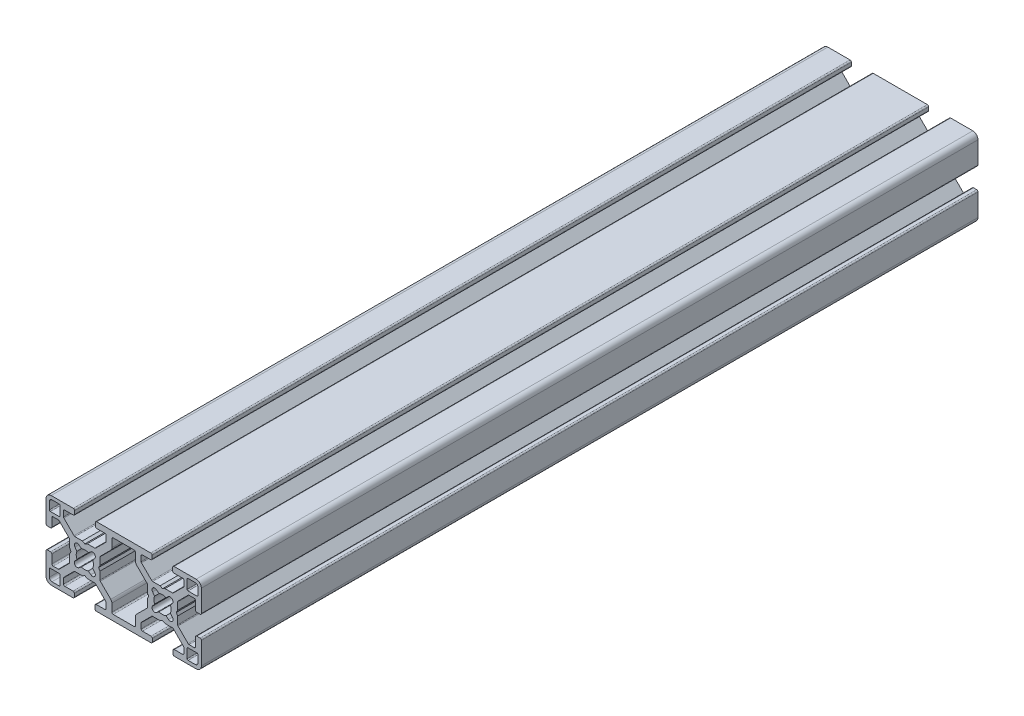
SolidWorks part; units mm, degrees
material "6105-T5 Aluminum"
ref_plane "Front Plane" through (0, 0, 0) normal (0, 0, 1) x (1, 0, 0)
ref_plane "Top Plane" through (0, 0, 0) normal (0, 1, 0) x (1, 0, 0)
ref_plane "Right Plane" through (0, 0, 0) normal (1, 0, 0) x (0, 0, -1)
sketch "Sketch1" plane through (0, 0, 0) normal (0, 0, -1) x (1, 0, 0)
  line L0 (13.319, 9.5) -> (9.88, 9.5)
  line L1 (9.5, 9.88) -> (9.5, 13.319)
  line L2 (9.881, 13.7) -> (12.7, 13.7)
  line L3 (13.7, 12.7) -> (13.7, 9.881)
  line L4 (13.7, -9.881) -> (13.7, -12.7)
  line L5 (12.7, -13.7) -> (9.881, -13.7)
  line L6 (9.5, -13.319) -> (9.5, -9.88)
  line L7 (9.88, -9.5) -> (13.319, -9.5)
  line L8 (1.3394, 3.0433) -> (2.3185, 3.8251)
  line L9 (3.8251, 2.3185) -> (3.0433, 1.3394)
  line L10 (3.0433, -1.3394) -> (3.8251, -2.3185)
  line L11 (2.3185, -3.8251) -> (1.3394, -3.0433)
  line L12 (-1.3292, -3.0477) -> (-2.3144, -3.8343)
  line L13 (-3.821, -2.3278) -> (-3.0392, -1.3486)
  line L14 (-3.0433, 1.3394) -> (-3.8251, 2.3185)
  line L15 (-2.3185, 3.8251) -> (-1.3394, 3.0433)
  line L16 (-10.45, 12.3) -> (-10.45, 9.2682)
  line L17 (-10.0106, 8.2075) -> (-5.9811, 4.178)
  line L18 (-5.8347, 3.8245) -> (-5.8347, 0.8875)
  line L19 (-5.8347, 0.8875) -> (-5.3247, -0.0625)
  line L20 (-5.3247, -0.0625) -> (-5.8347, -1.0125)
  line L21 (-5.8347, -1.0125) -> (-5.8347, -3.8245)
  line L22 (-5.9811, -4.178) -> (-10.0106, -8.2075)
  line L23 (-10.45, -9.2682) -> (-10.45, -12.3)
  line L24 (-10.95, -12.8) -> (-19.05, -12.8)
  line L25 (-19.55, -12.3) -> (-19.55, -9.2682)
  line L26 (-19.9893, -8.2075) -> (-24.0188, -4.178)
  line L27 (-24.1653, -3.8245) -> (-24.1653, -1.0125)
  line L28 (-24.1653, -1.0125) -> (-24.6753, -0.0625)
  line L29 (-24.6753, -0.0625) -> (-24.1653, 0.8875)
  line L30 (-24.1653, 0.8875) -> (-24.1653, 3.8245)
  line L31 (-24.0188, 4.178) -> (-19.9893, 8.2075)
  line L32 (-19.55, 9.2682) -> (-19.55, 12.3)
  line L33 (-19.05, 12.8) -> (-10.95, 12.8)
  line L34 (-28.6606, 3.0433) -> (-27.6814, 3.8251)
  line L35 (-26.1749, 2.3185) -> (-26.9566, 1.3394)
  line L36 (-26.9566, -1.3394) -> (-26.1749, -2.3185)
  line L37 (-27.6814, -3.8251) -> (-28.6606, -3.0433)
  line L38 (-31.3292, -3.0477) -> (-32.3143, -3.8343)
  line L39 (-33.8209, -2.3278) -> (-33.0391, -1.3486)
  line L40 (-33.0432, 1.3394) -> (-33.825, 2.3185)
  line L41 (-32.3184, 3.8251) -> (-31.3393, 3.0433)
  line L42 (-39.8809, -13.7) -> (-42.6999, -13.7)
  line L43 (-43.6999, -12.7) -> (-43.6999, -9.881)
  line L44 (-43.3189, -9.5) -> (-39.8799, -9.5)
  line L45 (-39.4999, -9.88) -> (-39.4999, -13.319)
  line L46 (-43.6999, 9.881) -> (-43.6999, 12.7)
  line L47 (-42.6999, 13.7) -> (-39.8809, 13.7)
  line L48 (-39.4999, 13.319) -> (-39.4999, 9.88)
  line L49 (-39.8799, 9.5) -> (-43.3189, 9.5)
  line L50 (-25.9374, -13.2425) -> (-25.9374, -14.5)
  line L51 (-25.4374, -15) -> (-4.5625, -15)
  line L52 (-4.0625, -14.5) -> (-4.0625, -13.2425)
  line L53 (-4.5625, -12.7425) -> (-7.7325, -12.7425)
  line L54 (-8.25, -12.2428) -> (-8.25, -10.2602)
  line L55 (-8.1035, -9.9067) -> (-4.178, -5.9811)
  line L56 (-3.8245, -5.8347) -> (-0.95, -5.8347)
  line L57 (-0.95, -5.8347) -> (0, -5.3247)
  line L58 (0, -5.3247) -> (0.95, -5.8347)
  line L59 (0.95, -5.8347) -> (3.8245, -5.8347)
  line L60 (4.178, -5.9811) -> (8.1035, -9.9067)
  line L61 (8.25, -10.2602) -> (8.25, -12.2428)
  line L62 (7.7325, -12.7425) -> (4.4375, -12.7425)
  line L63 (3.9375, -13.2425) -> (3.9375, -14.5)
  line L64 (4.4375, -15) -> (13, -15)
  line L65 (15, -13) -> (15, -4.5625)
  line L66 (14.5, -4.0625) -> (13.2425, -4.0625)
  line L67 (12.7425, -4.5625) -> (12.7425, -7.7325)
  line L68 (12.2428, -8.25) -> (10.2602, -8.25)
  line L69 (9.9067, -8.1035) -> (5.9811, -4.178)
  line L70 (5.8347, -3.8245) -> (5.8347, -1.0125)
  line L71 (5.8347, -1.0125) -> (5.3247, -0.0625)
  line L72 (5.3247, -0.0625) -> (5.8347, 0.8875)
  line L73 (5.8347, 0.8875) -> (5.8347, 3.8245)
  line L74 (5.9811, 4.178) -> (9.9067, 8.1035)
  line L75 (10.2602, 8.25) -> (12.2428, 8.25)
  line L76 (12.7425, 7.7325) -> (12.7425, 4.4375)
  line L77 (13.2425, 3.9375) -> (14.5, 3.9375)
  line L78 (15, 4.4375) -> (15, 13)
  line L79 (13, 15) -> (4.5625, 15)
  line L80 (4.0625, 14.5) -> (4.0625, 13.2425)
  line L81 (4.5625, 12.7425) -> (7.7325, 12.7425)
  line L82 (8.25, 12.2428) -> (8.25, 10.2602)
  line L83 (8.1035, 9.9067) -> (4.178, 5.9811)
  line L84 (3.8245, 5.8347) -> (0.95, 5.8347)
  line L85 (0.95, 5.8347) -> (0, 5.3247)
  line L86 (0, 5.3247) -> (-0.95, 5.8347)
  line L87 (-0.95, 5.8347) -> (-3.8245, 5.8347)
  line L88 (-4.178, 5.9811) -> (-8.1035, 9.9067)
  line L89 (-8.25, 10.2602) -> (-8.25, 12.2428)
  line L90 (-7.7325, 12.7425) -> (-4.4375, 12.7425)
  line L91 (-3.9375, 13.2425) -> (-3.9375, 14.5)
  line L92 (-4.4375, 15) -> (-25.5624, 15)
  line L93 (-26.0624, 14.5) -> (-26.0624, 13.2425)
  line L94 (-25.5624, 12.7425) -> (-22.2674, 12.7425)
  line L95 (-21.75, 12.2428) -> (-21.75, 10.2602)
  line L96 (-21.8964, 9.9067) -> (-25.8219, 5.9811)
  line L97 (-26.1755, 5.8347) -> (-29.0499, 5.8347)
  line L98 (-29.0499, 5.8347) -> (-29.9999, 5.3247)
  line L99 (-29.9999, 5.3247) -> (-30.9499, 5.8347)
  line L100 (-30.9499, 5.8347) -> (-33.8244, 5.8347)
  line L101 (-34.178, 5.9811) -> (-38.1035, 9.9067)
  line L102 (-38.2499, 10.2602) -> (-38.2499, 12.2428)
  line L103 (-37.7325, 12.7425) -> (-34.5624, 12.7425)
  line L104 (-34.0624, 13.2425) -> (-34.0624, 14.5)
  line L105 (-34.5624, 15) -> (-42.9999, 15)
  line L106 (-44.9999, 13) -> (-44.9999, 4.4375)
  line L107 (-44.4999, 3.9375) -> (-43.2424, 3.9375)
  line L108 (-42.7424, 4.4375) -> (-42.7424, 7.7325)
  line L109 (-42.2427, 8.25) -> (-40.2601, 8.25)
  line L110 (-39.9066, 8.1035) -> (-35.9811, 4.178)
  line L111 (-35.8346, 3.8245) -> (-35.8346, 0.8875)
  line L112 (-35.8346, 0.8875) -> (-35.3246, -0.0625)
  line L113 (-35.3246, -0.0625) -> (-35.8346, -1.0125)
  line L114 (-35.8346, -1.0125) -> (-35.8346, -3.8245)
  line L115 (-35.9811, -4.178) -> (-39.9066, -8.1035)
  line L116 (-40.2601, -8.25) -> (-42.2427, -8.25)
  line L117 (-42.7424, -7.7325) -> (-42.7424, -4.5625)
  line L118 (-43.2424, -4.0625) -> (-44.4999, -4.0625)
  line L119 (-44.9999, -4.5625) -> (-44.9999, -13)
  line L120 (-42.9999, -15) -> (-34.4374, -15)
  line L121 (-33.9374, -14.5) -> (-33.9374, -13.2425)
  line L122 (-34.4374, -12.7425) -> (-37.7325, -12.7425)
  line L123 (-38.2499, -12.2428) -> (-38.2499, -10.2602)
  line L124 (-38.1035, -9.9067) -> (-34.178, -5.9811)
  line L125 (-33.8244, -5.8347) -> (-30.9499, -5.8347)
  line L126 (-30.9499, -5.8347) -> (-29.9999, -5.3247)
  line L127 (-29.9999, -5.3247) -> (-29.0499, -5.8347)
  line L128 (-29.0499, -5.8347) -> (-26.1755, -5.8347)
  line L129 (-25.8219, -5.9811) -> (-21.8964, -9.9067)
  line L130 (-21.75, -10.2602) -> (-21.75, -12.2428)
  line L131 (-22.2674, -12.7425) -> (-25.4374, -12.7425)
  arc A0 (13.319, 9.5) -> (13.7, 9.881) centre (13.319, 9.881) ccw
  arc A1 (9.5, 9.88) -> (9.88, 9.5) centre (9.88, 9.88) ccw
  arc A2 (9.881, 13.7) -> (9.5, 13.319) centre (9.881, 13.319) ccw
  arc A3 (13.7, 12.7) -> (12.7, 13.7) centre (12.7, 12.7) ccw
  arc A4 (13.7, -9.881) -> (13.319, -9.5) centre (13.319, -9.881) ccw
  arc A5 (12.7, -13.7) -> (13.7, -12.7) centre (12.7, -12.7) ccw
  arc A6 (9.5, -13.319) -> (9.881, -13.7) centre (9.881, -13.319) ccw
  arc A7 (9.88, -9.5) -> (9.5, -9.88) centre (9.88, -9.88) ccw
  arc A8 (1.3394, 3.0433) -> (-1.3394, 3.0433) centre (0, 0) ccw
  arc A9 (3.8251, 2.3185) -> (2.3185, 3.8251) centre (2.9874, 2.9874) ccw
  arc A10 (3.0433, -1.3394) -> (3.0433, 1.3394) centre (0, 0) ccw
  arc A11 (2.3185, -3.8251) -> (3.8251, -2.3185) centre (2.9874, -2.9874) ccw
  arc A12 (-1.3292, -3.0477) -> (1.3394, -3.0433) centre (0, 0) ccw
  arc A13 (-3.821, -2.3278) -> (-2.3144, -3.8343) centre (-2.9833, -2.9966) ccw
  arc A14 (-3.0433, 1.3394) -> (-3.0392, -1.3486) centre (0, 0) ccw
  arc A15 (-2.3185, 3.8251) -> (-3.8251, 2.3185) centre (-2.9874, 2.9874) ccw
  arc A16 (-10.45, 12.3) -> (-10.95, 12.8) centre (-10.95, 12.3) ccw
  arc A17 (-10.45, 9.2682) -> (-10.0106, 8.2075) centre (-8.95, 9.2682) ccw
  arc A18 (-5.8347, 3.8245) -> (-5.9811, 4.178) centre (-6.3347, 3.8245) ccw
  arc A19 (-5.9811, -4.178) -> (-5.8347, -3.8245) centre (-6.3347, -3.8245) ccw
  arc A20 (-10.0106, -8.2075) -> (-10.45, -9.2682) centre (-8.95, -9.2682) ccw
  arc A21 (-10.95, -12.8) -> (-10.45, -12.3) centre (-10.95, -12.3) ccw
  arc A22 (-19.55, -12.3) -> (-19.05, -12.8) centre (-19.05, -12.3) ccw
  arc A23 (-19.55, -9.2682) -> (-19.9893, -8.2075) centre (-21.05, -9.2682) ccw
  arc A24 (-24.1653, -3.8245) -> (-24.0188, -4.178) centre (-23.6653, -3.8245) ccw
  arc A25 (-24.0188, 4.178) -> (-24.1653, 3.8245) centre (-23.6653, 3.8245) ccw
  arc A26 (-19.9893, 8.2075) -> (-19.55, 9.2682) centre (-21.05, 9.2682) ccw
  arc A27 (-19.05, 12.8) -> (-19.55, 12.3) centre (-19.05, 12.3) ccw
  arc A28 (-28.6606, 3.0433) -> (-31.3393, 3.0433) centre (-29.9999, 0) ccw
  arc A29 (-26.1749, 2.3185) -> (-27.6814, 3.8251) centre (-27.0126, 2.9874) ccw
  arc A30 (-26.9566, -1.3394) -> (-26.9566, 1.3394) centre (-29.9999, 0) ccw
  arc A31 (-27.6814, -3.8251) -> (-26.1749, -2.3185) centre (-27.0126, -2.9874) ccw
  arc A32 (-31.3292, -3.0477) -> (-28.6606, -3.0433) centre (-29.9999, 0) ccw
  arc A33 (-33.8209, -2.3278) -> (-32.3143, -3.8343) centre (-32.9832, -2.9966) ccw
  arc A34 (-33.0432, 1.3394) -> (-33.0391, -1.3486) centre (-29.9999, 0) ccw
  arc A35 (-32.3184, 3.8251) -> (-33.825, 2.3185) centre (-32.9873, 2.9874) ccw
  arc A36 (-39.8809, -13.7) -> (-39.4999, -13.319) centre (-39.8809, -13.319) ccw
  arc A37 (-43.6999, -12.7) -> (-42.6999, -13.7) centre (-42.6999, -12.7) ccw
  arc A38 (-43.3189, -9.5) -> (-43.6999, -9.881) centre (-43.3189, -9.881) ccw
  arc A39 (-39.4999, -9.88) -> (-39.8799, -9.5) centre (-39.8799, -9.88) ccw
  arc A40 (-43.6999, 9.881) -> (-43.3189, 9.5) centre (-43.3189, 9.881) ccw
  arc A41 (-42.6999, 13.7) -> (-43.6999, 12.7) centre (-42.6999, 12.7) ccw
  arc A42 (-39.4999, 13.319) -> (-39.8809, 13.7) centre (-39.8809, 13.319) ccw
  arc A43 (-39.8799, 9.5) -> (-39.4999, 9.88) centre (-39.8799, 9.88) ccw
  arc A44 (-25.4374, -12.7425) -> (-25.9374, -13.2425) centre (-25.4374, -13.2425) ccw
  arc A45 (-25.9374, -14.5) -> (-25.4374, -15) centre (-25.4374, -14.5) ccw
  arc A46 (-4.5625, -15) -> (-4.0625, -14.5) centre (-4.5625, -14.5) ccw
  arc A47 (-4.0625, -13.2425) -> (-4.5625, -12.7425) centre (-4.5625, -13.2425) ccw
  arc A48 (-8.25, -12.2428) -> (-7.7325, -12.7425) centre (-7.75, -12.2428) ccw
  arc A49 (-8.1035, -9.9067) -> (-8.25, -10.2602) centre (-7.75, -10.2602) ccw
  arc A50 (-3.8245, -5.8347) -> (-4.178, -5.9811) centre (-3.8245, -6.3347) ccw
  arc A51 (4.178, -5.9811) -> (3.8245, -5.8347) centre (3.8245, -6.3347) ccw
  arc A52 (8.25, -10.2602) -> (8.1035, -9.9067) centre (7.75, -10.2602) ccw
  arc A53 (7.7325, -12.7425) -> (8.25, -12.2428) centre (7.75, -12.2428) ccw
  arc A54 (4.4375, -12.7425) -> (3.9375, -13.2425) centre (4.4375, -13.2425) ccw
  arc A55 (3.9375, -14.5) -> (4.4375, -15) centre (4.4375, -14.5) ccw
  arc A56 (13, -15) -> (15, -13) centre (13, -13) ccw
  arc A57 (15, -4.5625) -> (14.5, -4.0625) centre (14.5, -4.5625) ccw
  arc A58 (13.2425, -4.0625) -> (12.7425, -4.5625) centre (13.2425, -4.5625) ccw
  arc A59 (12.2428, -8.25) -> (12.7425, -7.7325) centre (12.2428, -7.75) ccw
  arc A60 (9.9067, -8.1035) -> (10.2602, -8.25) centre (10.2602, -7.75) ccw
  arc A61 (5.8347, -3.8245) -> (5.9811, -4.178) centre (6.3347, -3.8245) ccw
  arc A62 (5.9811, 4.178) -> (5.8347, 3.8245) centre (6.3347, 3.8245) ccw
  arc A63 (10.2602, 8.25) -> (9.9067, 8.1035) centre (10.2602, 7.75) ccw
  arc A64 (12.7425, 7.7325) -> (12.2428, 8.25) centre (12.2428, 7.75) ccw
  arc A65 (12.7425, 4.4375) -> (13.2425, 3.9375) centre (13.2425, 4.4375) ccw
  arc A66 (14.5, 3.9375) -> (15, 4.4375) centre (14.5, 4.4375) ccw
  arc A67 (15, 13) -> (13, 15) centre (13, 13) ccw
  arc A68 (4.5625, 15) -> (4.0625, 14.5) centre (4.5625, 14.5) ccw
  arc A69 (4.0625, 13.2425) -> (4.5625, 12.7425) centre (4.5625, 13.2425) ccw
  arc A70 (8.25, 12.2428) -> (7.7325, 12.7425) centre (7.75, 12.2428) ccw
  arc A71 (8.1035, 9.9067) -> (8.25, 10.2602) centre (7.75, 10.2602) ccw
  arc A72 (3.8245, 5.8347) -> (4.178, 5.9811) centre (3.8245, 6.3347) ccw
  arc A73 (-4.178, 5.9811) -> (-3.8245, 5.8347) centre (-3.8245, 6.3347) ccw
  arc A74 (-8.25, 10.2602) -> (-8.1035, 9.9067) centre (-7.75, 10.2602) ccw
  arc A75 (-7.7325, 12.7425) -> (-8.25, 12.2428) centre (-7.75, 12.2428) ccw
  arc A76 (-4.4375, 12.7425) -> (-3.9375, 13.2425) centre (-4.4375, 13.2425) ccw
  arc A77 (-3.9375, 14.5) -> (-4.4375, 15) centre (-4.4375, 14.5) ccw
  arc A78 (-25.5624, 15) -> (-26.0624, 14.5) centre (-25.5624, 14.5) ccw
  arc A79 (-26.0624, 13.2425) -> (-25.5624, 12.7425) centre (-25.5624, 13.2425) ccw
  arc A80 (-21.75, 12.2428) -> (-22.2674, 12.7425) centre (-22.25, 12.2428) ccw
  arc A81 (-21.8964, 9.9067) -> (-21.75, 10.2602) centre (-22.25, 10.2602) ccw
  arc A82 (-26.1755, 5.8347) -> (-25.8219, 5.9811) centre (-26.1755, 6.3347) ccw
  arc A83 (-34.178, 5.9811) -> (-33.8244, 5.8347) centre (-33.8244, 6.3347) ccw
  arc A84 (-38.2499, 10.2602) -> (-38.1035, 9.9067) centre (-37.7499, 10.2602) ccw
  arc A85 (-37.7325, 12.7425) -> (-38.2499, 12.2428) centre (-37.7499, 12.2428) ccw
  arc A86 (-34.5624, 12.7425) -> (-34.0624, 13.2425) centre (-34.5624, 13.2425) ccw
  arc A87 (-34.0624, 14.5) -> (-34.5624, 15) centre (-34.5624, 14.5) ccw
  arc A88 (-42.9999, 15) -> (-44.9999, 13) centre (-42.9999, 13) ccw
  arc A89 (-44.9999, 4.4375) -> (-44.4999, 3.9375) centre (-44.4999, 4.4375) ccw
  arc A90 (-43.2424, 3.9375) -> (-42.7424, 4.4375) centre (-43.2424, 4.4375) ccw
  arc A91 (-42.2427, 8.25) -> (-42.7424, 7.7325) centre (-42.2427, 7.75) ccw
  arc A92 (-39.9066, 8.1035) -> (-40.2601, 8.25) centre (-40.2601, 7.75) ccw
  arc A93 (-35.8346, 3.8245) -> (-35.9811, 4.178) centre (-36.3346, 3.8245) ccw
  arc A94 (-35.9811, -4.178) -> (-35.8346, -3.8245) centre (-36.3346, -3.8245) ccw
  arc A95 (-40.2601, -8.25) -> (-39.9066, -8.1035) centre (-40.2601, -7.75) ccw
  arc A96 (-42.7424, -7.7325) -> (-42.2427, -8.25) centre (-42.2427, -7.75) ccw
  arc A97 (-42.7424, -4.5625) -> (-43.2424, -4.0625) centre (-43.2424, -4.5625) ccw
  arc A98 (-44.4999, -4.0625) -> (-44.9999, -4.5625) centre (-44.4999, -4.5625) ccw
  arc A99 (-44.9999, -13) -> (-42.9999, -15) centre (-42.9999, -13) ccw
  arc A100 (-34.4374, -15) -> (-33.9374, -14.5) centre (-34.4374, -14.5) ccw
  arc A101 (-33.9374, -13.2425) -> (-34.4374, -12.7425) centre (-34.4374, -13.2425) ccw
  arc A102 (-38.2499, -12.2428) -> (-37.7325, -12.7425) centre (-37.7499, -12.2428) ccw
  arc A103 (-38.1035, -9.9067) -> (-38.2499, -10.2602) centre (-37.7499, -10.2602) ccw
  arc A104 (-33.8244, -5.8347) -> (-34.178, -5.9811) centre (-33.8244, -6.3347) ccw
  arc A105 (-25.8219, -5.9811) -> (-26.1755, -5.8347) centre (-26.1755, -6.3347) ccw
  arc A106 (-21.75, -10.2602) -> (-21.8964, -9.9067) centre (-22.25, -10.2602) ccw
  arc A107 (-22.2674, -12.7425) -> (-21.75, -12.2428) centre (-22.25, -12.2428) ccw
extrude "Extrude1" add sketch "Sketch1" along normal blind 300
